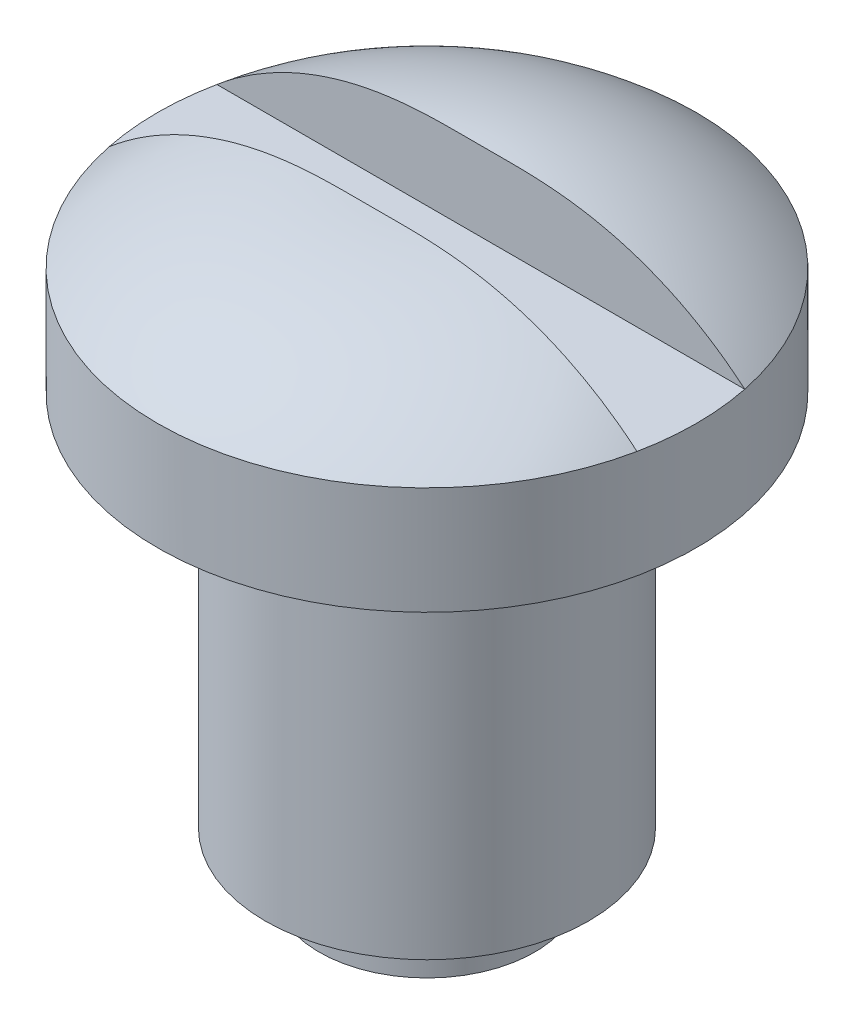
SolidWorks part; units mm, degrees
material "AISI 1020 Steel, Cold Rolled"
ref_plane "Front Plane" through (0, 0, 0) normal (0, 0, 1) x (1, 0, 0)
ref_plane "Top Plane" through (0, 0, 0) normal (0, 1, 0) x (1, 0, 0)
ref_plane "Right Plane" through (0, 0, 0) normal (1, 0, 0) x (0, 0, -1)
sketch "Sketch1" plane through (0, 0, 0) normal (0, 0, 1) x (1, 0, 0)
  line L0 (0, 0) -> (0, 50000) construction
  line L1 (0, 6.1021) -> (0, -3.3661)
  line L2 (0, 6.1021) -> (-1, 6.1021)
  line L3 (-3, -3.3661) -> (-2, -3.3661)
  line L4 (-3, 3.6339) -> (-3, -3.3661)
  line L5 (0, 0) -> (-3, -3.3661) construction
  line L6 (0, 0) -> (-3, 3.6339) construction
  line L7 (-3, 3.6339) -> (-5, 3.6339)
  line L8 (-5, 3.6339) -> (-5, 5.6339)
  line L9 (-1, 6.1021) -> (-1, 7.1021)
  line L10 (0, -4.3661) -> (-2, -4.3661)
  line L11 (-2, -4.3661) -> (-2, -3.3661)
  line L12 (0, -3.3661) -> (0, -4.3661)
  arc A0 (-5, 5.6339) -> (-1, 7.1021) centre (-1.0673, 1.1025) cw
  point P0 (0, 0)
  dimension "D6" = 1.0673
  dimension "D8" = 2
  dimension "D11" = 6
  dimension "D1" = 1
  dimension "D2" = 3
  dimension "D3" = 2
  dimension "D4" = 2
  dimension "D5" = 1
  dimension "D7" = 3.3661
  dimension "D9" = 1
  dimension "D10" = 7
revolve "Revolve2" add sketch "Sketch1" angle 360 about L1
ref_plane "Plane1" through (-5, 0, 0) normal (-1, 0, 0) x (0, 0, 1)
sketch "Sketch2" plane through (-5, 0, 0) normal (-1, 0, 0) x (0, 0, 1)
  line L1 (-1, 7.1539) -> (-1, 7.7877)
  line L2 (-1, 7.1021) -> (-1, 5.6339)
  line L3 (5, 5.6339) -> (-5, 5.6339) construction
  line L4 (-1, 5.6339) -> (1, 5.6339)
  line L5 (1, 5.6339) -> (1, 7.1021)
  line L6 (-1, 7.7877) -> (1, 7.7877)
  line L7 (1, 7.1021) -> (1, 7.7877)
  line L8 (-1, 7.1021) -> (-1, 7.1539)
  dimension "D1" = 7.7877
  dimension "D2" = 1
  dimension "D3" = 1
extrude "Cut-Extrude6" cut sketch "Sketch2" against normal blind 10
